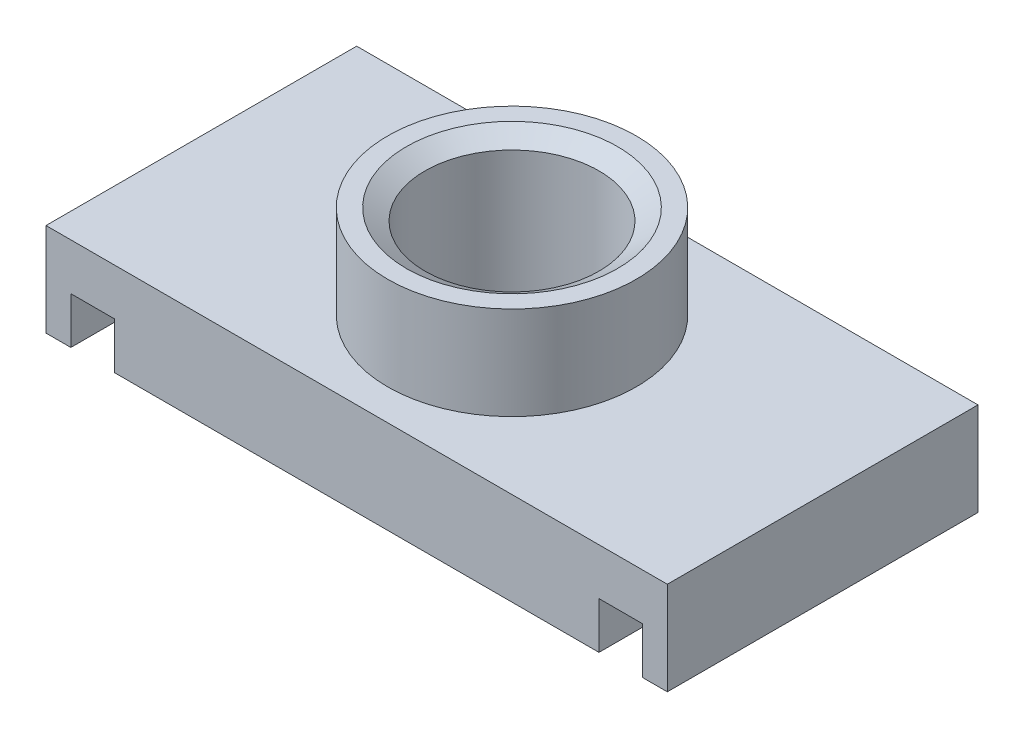
SolidWorks part; units mm, degrees
ref_plane "Front Plane" through (0, 0, 0) normal (0, 0, 1) x (1, 0, 0)
ref_plane "Top Plane" through (0, 0, 0) normal (0, 1, 0) x (1, 0, 0)
ref_plane "Right Plane" through (0, 0, 0) normal (1, 0, 0) x (0, 0, -1)
sketch "Sketch1" plane through (0, 0, 0) normal (0, 1, 0) x (1, 0, 0)
  circle A0 centre (0, 0) radius 14
  circle A1 centre (0, 0) radius 20
  dimension "D1" = 28
  dimension "D2" = 40
extrude "Boss-Extrude1" add sketch "Sketch1" along normal blind 30
sketch "Sketch3" plane through (0, 0, 0) normal (0, 0, 1) x (1, 0, 0)
  line L0 (0, 30) -> (-17, 30)
  line L1 (14, 30) -> (-14, 30) construction
  line L2 (20, 30) -> (-20, 30) construction
  line L3 (-17, 30) -> (-0.0369, 19.4051)
  line L4 (-0.0369, 19.4051) -> (0, 30)
  line L5 (-17, 30) -> (-17, 34.7473)
  line L6 (-17, 34.7473) -> (0, 34.7473)
  line L7 (0, 34.7473) -> (0, 30)
  dimension "D1" = 17
  dimension "D2" = 20
revolve "Cut-Revolve2" cut sketch "Sketch3" angle 360 about L7
sketch "Sketch4" plane through (0, 0, 0) normal (0, 1, 0) x (1, 0, 0)
  line L1 (-50, 25) -> (50, 25)
  line L2 (-50, 25) -> (-50, -25)
  line L3 (-50, -25) -> (50, -25)
  line L4 (50, 25) -> (50, -25)
  line L5 (0, -25) -> (0, 25) construction
  line L6 (-50, 0) -> (50, 0) construction
  circle A0 centre (0, 0) radius 14
  point P0 (0, 0)
  dimension "D3" = 28
  dimension "D1" = 50
  dimension "D2" = 100
extrude "Boss-Extrude2" add sketch "Sketch4" along normal blind 15
sketch "Sketch5" plane through (0, 0, 0) normal (0, 0, 1) x (1, 0, 0)
  line L0 (-50, 0) -> (50, 0) construction
  line L1 (-39, -7.5) -> (-46, -7.5)
  line L2 (-39, -7.5) -> (-39, 7.5)
  line L3 (-39, 7.5) -> (-46, 7.5)
  line L4 (-46, -7.5) -> (-46, 7.5)
  line L5 (-42.5, 7.5) -> (-42.5, -7.5) construction
  line L6 (-39, 0) -> (-46, 0) construction
  line L7 (0, -16.5) -> (0, 16.5) construction
  line L8 (39, 0) -> (46, 0) construction
  line L9 (42.5, 7.5) -> (42.5, -7.5) construction
  line L10 (46, -7.5) -> (46, 7.5)
  line L11 (39, 7.5) -> (46, 7.5)
  line L12 (39, -7.5) -> (39, 7.5)
  line L13 (39, -7.5) -> (46, -7.5)
  point P0 (-42.5, 0)
  point P19 (42.5, 0)
  dimension "D1" = 15
  dimension "D2" = 7
  dimension "D3" = 42.5
extrude "Cut-Extrude2" cut sketch "Sketch5" against normal through all both and the other way through all
